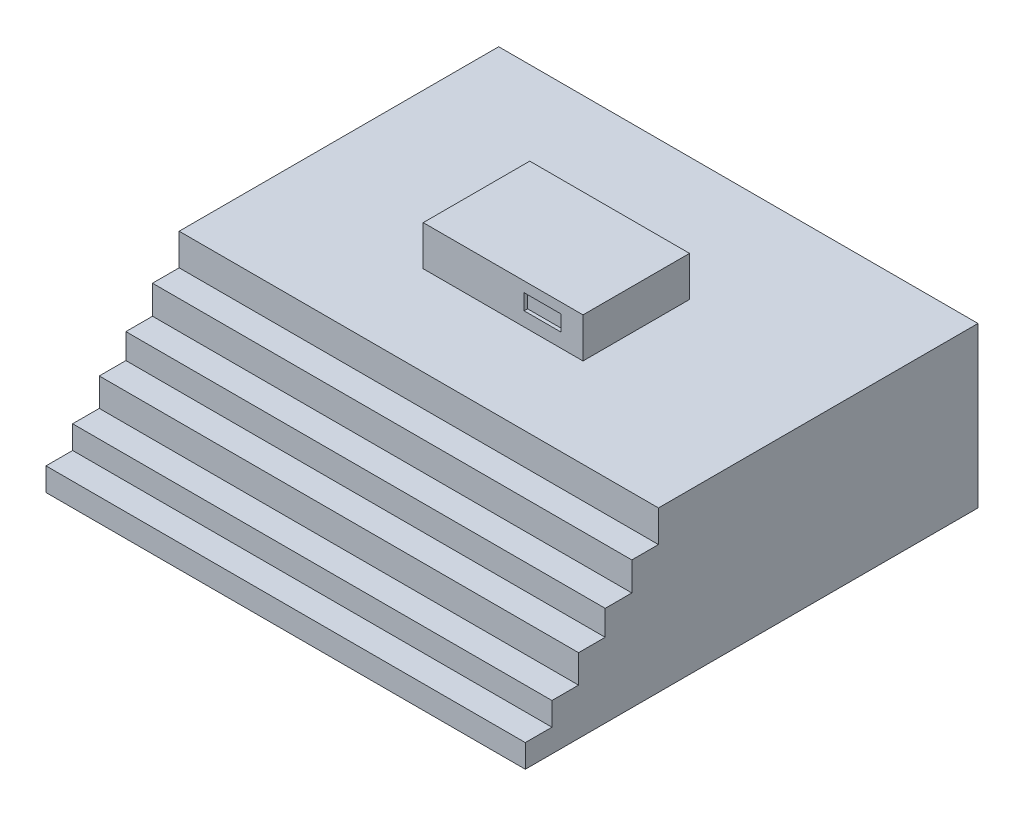
SolidWorks part; units mm, degrees
ref_plane "Front Plane" through (0, 0, 0) normal (0, 0, 1) x (1, 0, 0)
ref_plane "Top Plane" through (0, 0, 0) normal (0, 1, 0) x (1, 0, 0)
ref_plane "Right Plane" through (0, 0, 0) normal (1, 0, 0) x (0, 0, -1)
sketch "Sketch2" plane through (0, 0, 0) normal (0, 0, 1) x (1, 0, 0)
  line L1 (-142.7079, 785.765) -> (771.6921, 785.765)
  line L2 (-142.7079, 785.765) -> (-142.7079, 480.965)
  line L3 (-142.7079, 480.965) -> (771.6921, 480.965)
  line L4 (771.6921, 785.765) -> (771.6921, 480.965)
  dimension "D1" = 304.8
  dimension "D2" = 914.4
extrude "Boss-Extrude3" add sketch "Sketch2" along normal blind 609.6
sketch "Sketch3" plane through (0, 0, 609.6) normal (0, 0, 1) x (1, 0, 0)
  line L0 (-142.7079, 785.765) -> (-142.7079, 480.965) construction
  line L1 (-142.7079, 725.2673) -> (771.6921, 725.2673)
  line L2 (-142.7079, 725.2673) -> (-142.7079, 480.965)
  line L3 (-142.7079, 480.965) -> (771.6921, 480.965)
  line L4 (771.6921, 725.2673) -> (771.6921, 480.965)
extrude "Boss-Extrude4" add sketch "Sketch3" along normal blind 50.8
sketch "Sketch4" plane through (0, 0, 660.4) normal (0, 0, 1) x (1, 0, 0)
  line L0 (-142.7079, 725.2673) -> (-142.7079, 480.965) construction
  line L1 (-142.7079, 670.7003) -> (771.6921, 670.7003)
  line L2 (-142.7079, 670.7003) -> (-142.7079, 480.965)
  line L3 (-142.7079, 480.965) -> (771.6921, 480.965)
  line L4 (771.6921, 670.7003) -> (771.6921, 480.965)
extrude "Boss-Extrude5" add sketch "Sketch4" along normal blind 50.8
sketch "Sketch5" plane through (0, 0, 711.2) normal (0, 0, 1) x (1, 0, 0)
  line L0 (-142.7079, 670.7003) -> (-142.7079, 480.965) construction
  line L1 (-142.7079, 622.8345) -> (771.6921, 622.8345)
  line L2 (-142.7079, 622.8345) -> (-142.7079, 480.965)
  line L3 (-142.7079, 480.965) -> (771.6921, 480.965)
  line L4 (771.6921, 622.8345) -> (771.6921, 480.965)
  line L5 (-142.7079, 480.965) -> (771.6921, 480.965) construction
extrude "Boss-Extrude6" add sketch "Sketch5" along normal blind 50.8
sketch "Sketch6" plane through (0, 0, 762) normal (0, 0, 1) x (1, 0, 0)
  line L0 (-142.7079, 622.8345) -> (-142.7079, 480.965) construction
  line L1 (-142.7079, 569.2248) -> (771.6921, 569.2248)
  line L2 (-142.7079, 569.2248) -> (-142.7079, 480.965)
  line L3 (-142.7079, 480.965) -> (771.6921, 480.965)
  line L4 (771.6921, 569.2248) -> (771.6921, 480.965)
  line L5 (-142.7079, 480.965) -> (771.6921, 480.965) construction
extrude "Boss-Extrude7" add sketch "Sketch6" along normal blind 50.8
sketch "Sketch7" plane through (0, 0, 812.8) normal (0, 0, 1) x (1, 0, 0)
  line L0 (-142.7079, 569.2248) -> (-142.7079, 480.965) construction
  line L1 (-142.7079, 525.0949) -> (771.6921, 525.0949)
  line L2 (-142.7079, 525.0949) -> (-142.7079, 480.965)
  line L3 (-142.7079, 480.965) -> (771.6921, 480.965)
  line L4 (771.6921, 525.0949) -> (771.6921, 480.965)
extrude "Boss-Extrude8" add sketch "Sketch7" along normal blind 50.8
sketch "Sketch8" plane through (0, 785.765, 0) normal (0, 1, 0) x (1, 0, 0)
  line L1 (152.1407, -235.5959) -> (456.9407, -235.5959)
  line L2 (152.1407, -235.5959) -> (152.1407, -438.7959)
  line L3 (152.1407, -438.7959) -> (456.9407, -438.7959)
  line L4 (456.9407, -235.5959) -> (456.9407, -438.7959)
  dimension "D1" = 203.2
  dimension "D2" = 304.8
extrude "Boss-Extrude9" add sketch "Sketch8" along normal blind 76.2 contours L2 L1 L4 L3
sketch "Sketch9" plane through (0, 0, 438.7959) normal (0, 0, 1) x (1, 0, 0)
  line L1 (344.7071, 842.488) -> (414.7071, 842.488)
  line L2 (344.7071, 842.488) -> (344.7071, 812.488)
  line L3 (344.7071, 812.488) -> (414.7071, 812.488)
  line L4 (414.7071, 842.488) -> (414.7071, 812.488)
  dimension "D1" = 70
  dimension "D2" = 30
extrude "Cut-Extrude1" cut sketch "Sketch9" against normal blind 6.604
